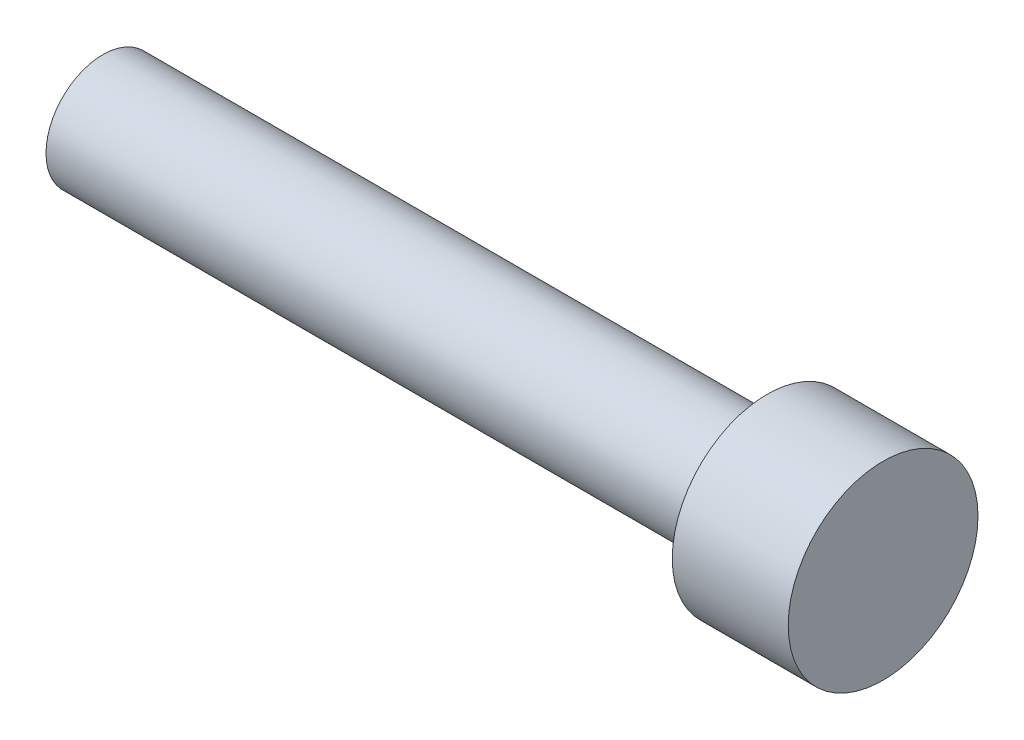
SolidWorks part; units mm, degrees
ref_plane "정면" through (0, 0, 0) normal (0, 0, 1) x (1, 0, 0)
ref_plane "윗면" through (0, 0, 0) normal (0, 1, 0) x (1, 0, 0)
ref_plane "우측면" through (0, 0, 0) normal (1, 0, 0) x (0, 0, -1)
sketch "스케치1" plane through (0, 0, 0) normal (0, 0, 1) x (1, 0, 0)
  line L0 (0, 0) -> (53.9379, 0) construction
  line L1 (-17.5, 0) -> (23.61, 0)
  line L2 (-17.5, 3) -> (17.5, 3)
  line L3 (-17.5, 3) -> (-17.5, -3)
  line L4 (-17.5, -3) -> (17.5, -3)
  line L5 (17.5, 3) -> (17.5, -3)
  line L6 (-17.5, 3) -> (17.5, -3) construction
  line L7 (-17.5, -3) -> (17.5, 3) construction
  line L8 (11.39, 5) -> (23.61, 5)
  line L9 (11.39, 5) -> (11.39, -5)
  line L10 (11.39, -5) -> (23.61, -5)
  line L11 (23.61, 5) -> (23.61, -5)
  line L12 (11.39, 5) -> (23.61, -5) construction
  line L13 (11.39, -5) -> (23.61, 5) construction
  line L14 (17.5, 3) -> (17.5, 5)
  line L15 (17.5, -3) -> (17.5, -5)
  point P7 (17.5, 0)
  dimension "D1" = 6.11
  dimension "D2" = 10
  dimension "D3" = 35
  dimension "D4" = 6
revolve "회전1" add sketch "스케치1" angle 360 about L0
